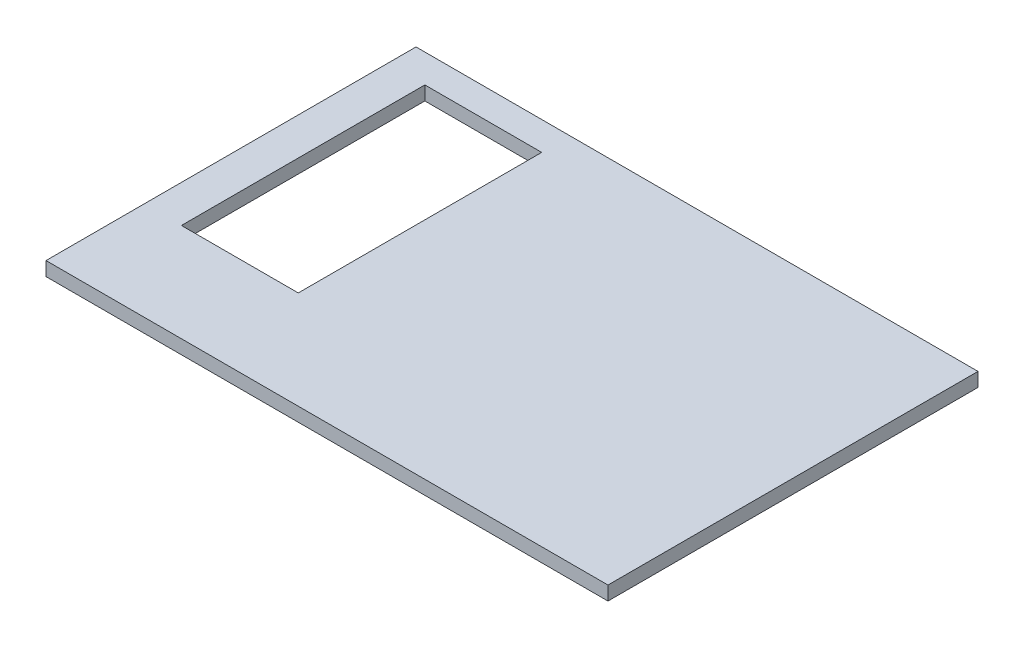
SolidWorks part; units mm, degrees
ref_plane "Front Plane" through (0, 0, 0) normal (0, 0, 1) x (1, 0, 0)
ref_plane "Top Plane" through (0, 0, 0) normal (0, 1, 0) x (1, 0, 0)
ref_plane "Right Plane" through (0, 0, 0) normal (1, 0, 0) x (0, 0, -1)
sketch "Sketch1" plane through (0, 0, 0) normal (0, 1, 0) x (1, 0, 0)
  line L1 (0, 0) -> (202, 0)
  line L2 (0, 0) -> (0, 133)
  line L3 (0, 133) -> (202, 133)
  line L4 (202, 0) -> (202, 133)
  line L5 (13.4171, 122.76) -> (55.4171, 122.76)
  line L6 (13.4171, 122.76) -> (13.4171, 35.26)
  line L7 (13.4171, 35.26) -> (55.4171, 35.26)
  line L8 (55.4171, 122.76) -> (55.4171, 35.26)
  dimension "D1" = 202
  dimension "D2" = 133
extrude "Boss-Extrude2" add sketch "Sketch1" along normal blind 5
